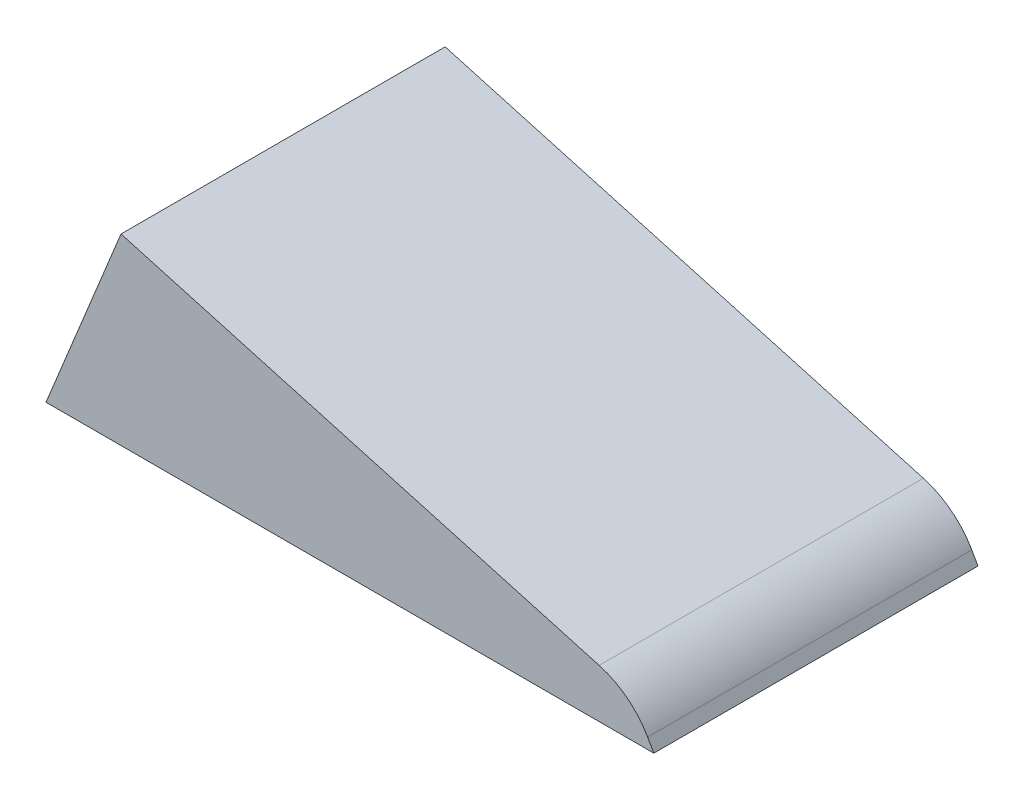
SolidWorks part; units mm, degrees
ref_plane "Front Plane" through (0, 0, 0) normal (0, 0, 1) x (1, 0, 0)
ref_plane "Top Plane" through (0, 0, 0) normal (0, 1, 0) x (1, 0, 0)
ref_plane "Right Plane" through (0, 0, 0) normal (1, 0, 0) x (0, 0, -1)
sketch "Sketch1" plane through (0, 0, 0) normal (0, 0, 1) x (1, 0, 0)
  line L0 (-87.8175, -54.6718) -> (-40.8117, 60.1802)
  line L1 (-40.8117, 60.1802) -> (278.9778, -29.7727)
  line L2 (278.9778, -29.7727) -> (293.1825, -54.6718)
  line L3 (293.1825, -54.6718) -> (-87.8175, -54.6718)
extrude "Boss-Extrude1" add sketch "Sketch1" along normal blind 203.2
fillet "Fillet1" radius 50.8 1 edges at (278.9778, -29.7727, 101.6)
